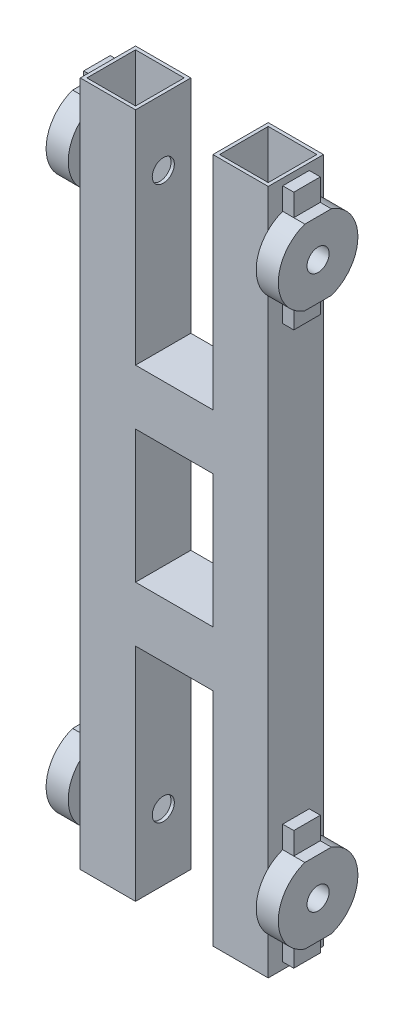
SolidWorks part; units mm, degrees
ref_plane "Front Plane" through (0, 0, 0) normal (0, 0, 1) x (1, 0, 0)
ref_plane "Top Plane" through (0, 0, 0) normal (0, 1, 0) x (1, 0, 0)
ref_plane "Right Plane" through (0, 0, 0) normal (1, 0, 0) x (0, 0, -1)
sketch "Sketch1" plane through (0, 0, 0) normal (0, 1, 0) x (1, 0, 0)
  line L0 (0, 63.6278) -> (0, -69.3975) construction
  line L1 (-105.4586, 0) -> (105.4586, 0) construction
  line L2 (19.5, 10.942) -> (19.5, -11.058)
  line L3 (18, 12.442) -> (43, 12.442)
  line L4 (18, 12.442) -> (18, -12.558)
  line L5 (18, -12.558) -> (43, -12.558)
  line L6 (43, 12.442) -> (43, -12.558)
  line L7 (19.5, -11.058) -> (41.5, -11.058)
  line L8 (41.5, 10.942) -> (41.5, -11.058)
  line L13 (19.5, 10.942) -> (41.5, 10.942)
  point P5 (30.442, 0)
  point P10 (30.5, -0.058)
  dimension "D1" = 25
  dimension "D2" = 25
  dimension "D3" = 18
  dimension "D4" = 1.5
extrude "Boss-Extrude1" add sketch "Sketch1" along normal blind 310
sketch "Sketch2" plane through (18, 0, 0) normal (-1, 0, 0) x (0, 0, 1)
  line L5 (12.558, 310) -> (12.558, 0) construction
  line L6 (-12.442, 210) -> (12.558, 210)
  line L7 (-12.442, 210) -> (-12.442, 185)
  line L8 (-12.442, 185) -> (12.558, 185)
  line L9 (12.558, 210) -> (12.558, 185)
  line L10 (-12.442, 210) -> (12.558, 185) construction
  line L11 (-12.442, 185) -> (12.558, 210) construction
  line L12 (-12.442, 310) -> (12.558, 310) construction
  line L13 (-10.942, 208.5) -> (-10.942, 186.5)
  line L14 (-12.442, 125) -> (12.558, 125)
  line L15 (-12.442, 125) -> (-12.442, 100)
  line L16 (-12.442, 100) -> (12.558, 100)
  line L17 (12.558, 125) -> (12.558, 100)
  line L18 (-12.442, 125) -> (12.558, 100) construction
  line L19 (-12.442, 100) -> (12.558, 125) construction
  line L20 (-10.942, 186.5) -> (11.058, 186.5)
  line L21 (11.058, 208.5) -> (11.058, 186.5)
  line L22 (-10.942, 208.5) -> (11.058, 208.5)
  line L23 (-10.942, 123.5) -> (-10.942, 101.5)
  line L24 (-10.942, 101.5) -> (11.058, 101.5)
  line L25 (11.058, 123.5) -> (11.058, 101.5)
  line L26 (-10.942, 123.5) -> (11.058, 123.5)
  point P0 (0.058, 197.5)
  point P9 (0.058, 112.5)
  dimension "D1" = 25
  dimension "D2" = 25
  dimension "D3" = 100
  dimension "D4" = 25
  dimension "D5" = 25
  dimension "D8" = 60
  dimension "D6" = 1.5
  dimension "D7" = 1.5
extrude "Boss-Extrude2" add sketch "Sketch2" along normal blind 17.5
sketch "Sketch8" plane through (18, 0, 0) normal (-1, 0, 0) x (0, 0, 1)
  line L0 (0, 340.3057) -> (0, -30.6599) construction
  line L1 (-12.442, 310) -> (12.558, 310) construction
  line L2 (-12.442, 0) -> (12.558, 0) construction
  circle A0 centre (0, 280) radius 5
  circle A1 centre (0, 30) radius 5
  dimension "D1" = 30
  dimension "D2" = 30
extrude "Cut-Extrude1" cut sketch "Sketch8" against normal blind 25
sketch "Sketch9" plane through (43, 0, 0) normal (1, 0, 0) x (0, 0, -1)
  line L0 (-6, 13.0294) -> (-6, 3.0294)
  line L24 (-6, 3.0294) -> (6, 3.0294)
  line L25 (6, 3.0294) -> (6, 13.0294)
  line L26 (-6, 46.9706) -> (-6, 56.9706)
  line L27 (-6, 56.9706) -> (6, 56.9706)
  line L28 (6, 56.9706) -> (6, 46.9706)
  circle A4 centre (0, 30) radius 5
  circle A5 centre (0, 30) radius 18
  arc A6 (-6, 46.9706) -> (6, 46.9706) centre (0, 30) cw
  arc A7 (-6, 13.0294) -> (6, 13.0294) centre (0, 30) ccw
  circle M17 centre (0, 30) radius 5
  line M21 (-12.558, 310) -> (-12.558, 0)
  dimension "D1" = 10
  dimension "D5" = 10
  dimension "D3" = 12
  dimension "D2" = 10
  dimension "D4" = 12
extrude "Boss-Extrude3" add sketch "Sketch9" along normal blind 10 contours A5 M17 | A5 L0 L24 L25 | A5 M21 | A5 L28 L27 L26 | A4
sketch "Sketch10" plane through (43, 0, 0) normal (1, 0, 0) x (0, 0, -1)
  line L0 (-6, 296.9706) -> (-6, 306.9706)
  line L1 (-6, 306.9706) -> (6, 306.9706)
  line L2 (6, 306.9706) -> (6, 296.9706)
  line L3 (-6, 263.0294) -> (-6, 253.0294)
  line L4 (-6, 253.0294) -> (6, 253.0294)
  line L5 (6, 253.0294) -> (6, 263.0294)
  circle A0 centre (0, 280) radius 18
  arc A1 (-6, 296.9706) -> (6, 296.9706) centre (0, 280) cw
  arc A2 (-6, 263.0294) -> (6, 263.0294) centre (0, 280) ccw
  circle A3 centre (0, 280) radius 5
  dimension "D1" = 12
  dimension "D2" = 10
  dimension "D3" = 10
  dimension "D4" = 10
  dimension "D5" = 12
  dimension "D6" = 10
extrude "Boss-Extrude4" add sketch "Sketch10" along normal blind 10
sketch "Sketch11" plane through (53, 0, 0) normal (1, 0, 0) x (0, 0, -1)
  line L0 (-6, 13.0294) -> (6, 13.0294)
  line L1 (6, 13.0294) -> (6, 3.0294)
  line L2 (-6, 3.0294) -> (6, 3.0294) construction
  line L3 (6, 3.0294) -> (6, 13.0294) construction
  line L4 (6, 3.0294) -> (-6, 3.0294)
  line L5 (-6, 3.0294) -> (-6, 13.0294)
  line L6 (-6, 46.9706) -> (6, 46.9706)
  line L7 (6, 46.9706) -> (6, 56.9706)
  line L8 (6, 56.9706) -> (-6, 56.9706)
  line L9 (-6, 56.9706) -> (-6, 46.9706)
  line L10 (-6, 263.0294) -> (-6, 253.0294)
  line L11 (-6, 253.0294) -> (6, 253.0294)
  line L12 (6, 253.0294) -> (6, 263.0294)
  line L13 (6, 263.0294) -> (-6, 263.0294)
  line L14 (-6, 296.9706) -> (-6, 306.9706)
  line L15 (-6, 306.9706) -> (6, 306.9706)
  line L16 (6, 306.9706) -> (6, 296.9706)
  line L17 (6, 296.9706) -> (-6, 296.9706)
  arc A0 (-6, 46.9706) -> (-6, 13.0294) centre (0, 30) ccw construction
extrude "Cut-Extrude2" cut sketch "Sketch11" against normal blind 5
mirror "Mirror1" about plane through (0.5, 0, 0) normal (-1, 0, 0) of "Cut-Extrude2", "Boss-Extrude1", "Boss-Extrude2", "Cut-Extrude1", "Boss-Extrude3", "Boss-Extrude4"
